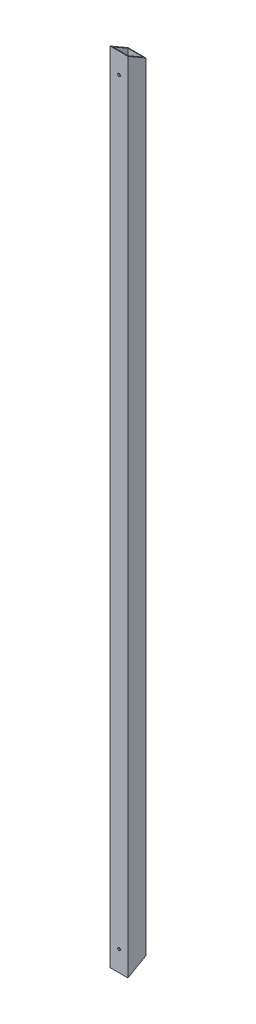
SolidWorks part; units mm, degrees
material "6061 Alloy"
ref_plane "Front Plane" through (0, 0, 0) normal (0, 0, 1) x (1, 0, 0)
ref_plane "Top Plane" through (0, 0, 0) normal (0, 1, 0) x (1, 0, 0)
ref_plane "Right Plane" through (0, 0, 0) normal (1, 0, 0) x (0, 0, -1)
sketch "Sketch1" plane through (0, 0, 0) normal (0, 0, 1) x (1, 0, 0)
  line L1 (-22.225, 990.092) -> (22.225, 990.092)
  line L2 (-22.225, 990.092) -> (-22.225, -990.092)
  line L3 (-22.225, -990.092) -> (22.225, -990.092)
  line L4 (22.225, 990.092) -> (22.225, -990.092)
  line L5 (-22.225, 990.092) -> (22.225, -990.092) construction
  line L6 (-22.225, -990.092) -> (22.225, 990.092) construction
  point P0 (0, 0)
  dimension "D1" = 44.45
  dimension "D2" = 1980.184
extrude "Boss-Extrude1" add sketch "Sketch1" along normal blind 44.45
sketch "Sketch2" plane through (0, 990.092, 0) normal (0, 1, 0) x (1, 0, 0)
  line L0 (22.225, 0) -> (-22.225, 0) construction
  line L1 (-19.05, -3.175) -> (19.05, -3.175)
  line L2 (-19.05, -3.175) -> (-19.05, -41.275)
  line L3 (-19.05, -41.275) -> (19.05, -41.275)
  line L4 (19.05, -3.175) -> (19.05, -41.275)
  line L5 (-19.05, -3.175) -> (19.05, -41.275) construction
  line L6 (-19.05, -41.275) -> (19.05, -3.175) construction
  line L7 (22.225, -44.45) -> (-22.225, -44.45) construction
  line L8 (-22.225, -44.45) -> (-22.225, 0) construction
  line L9 (22.225, -44.45) -> (22.225, 0) construction
  point P0 (0, -22.225)
  dimension "D1" = 3.175
  dimension "D2" = 3.175
  dimension "D3" = 3.175
  dimension "D4" = 3.175
extrude "Cut-Extrude1" cut sketch "Sketch2" against normal through all
sketch "Sketch3" plane through (22.225, 0, 0) normal (1, 0, 0) x (0, 0, -1)
  line L0 (-44.45, 990.092) -> (0, 964.4288)
  line L1 (0, -990.092) -> (0, 990.092) construction
  line L2 (0, 964.4288) -> (0, 990.092)
  line L3 (0, 990.092) -> (-44.45, 990.092)
  line L4 (-44.45, -990.092) -> (0, -964.4288)
  line L5 (0, -964.4288) -> (0, -990.092)
  line L6 (0, -990.092) -> (-44.45, -990.092)
  dimension "D1" = 60
  dimension "D2" = 60
extrude "Cut-Extrude2" cut sketch "Sketch3" against normal through all
ref_plane "Plane1" through (22.225, 964.4288, 0) normal (0, 1, 0) x (1, 0, 0)
sketch "Sketch13" plane through (0, 0, 44.45) normal (0, 0, 1) x (1, 0, 0)
  line L0 (-22.225, -990.092) -> (22.225, -990.092) construction
  line L1 (-22.225, 990.092) -> (-22.225, -990.092) construction
  line L2 (22.225, 990.092) -> (-22.225, 990.092) construction
  circle A0 centre (0, 939.038) radius 3.3734
  circle A1 centre (0, -939.038) radius 3.3734
  dimension "D1" = 6.7469
  dimension "D4" = 6.7469
  dimension "D2" = 51.054
  dimension "D3" = 22.225
  dimension "D5" = 22.225
  dimension "D6" = 51.054
extrude "Cut-Extrude7" cut sketch "Sketch13" against normal through all
sketch "Sketch15" plane through (0, 0, 44.45) normal (0, 0, 1) x (1, 0, 0)
  line L0 (22.225, 990.092) -> (-22.225, 990.092) construction
  line L6 (-22.225, -990.092) -> (22.225, -990.092) construction
  line L8 (-22.225, 990.092) -> (-22.225, -990.092) construction
  point P5 (-9.525, 518.1854)
  point P8 (9.525, 518.1854)
  point P11 (9.525, 612.1654)
  point P14 (-9.525, 612.1654)
  point P25 (-9.525, -612.1654)
  point P26 (9.525, -612.1654)
  point P27 (9.525, -518.1854)
  point P28 (-9.525, -518.1854)
  dimension "D1" = 377.9266
  dimension "D2" = 377.9266
  dimension "D3" = 471.9066
  dimension "D4" = 471.9066
  dimension "D5" = 12.7
  dimension "D6" = 31.75
  dimension "D7" = 377.9266
  dimension "D8" = 377.9266
  dimension "D9" = 471.9066
  dimension "D10" = 471.9066
